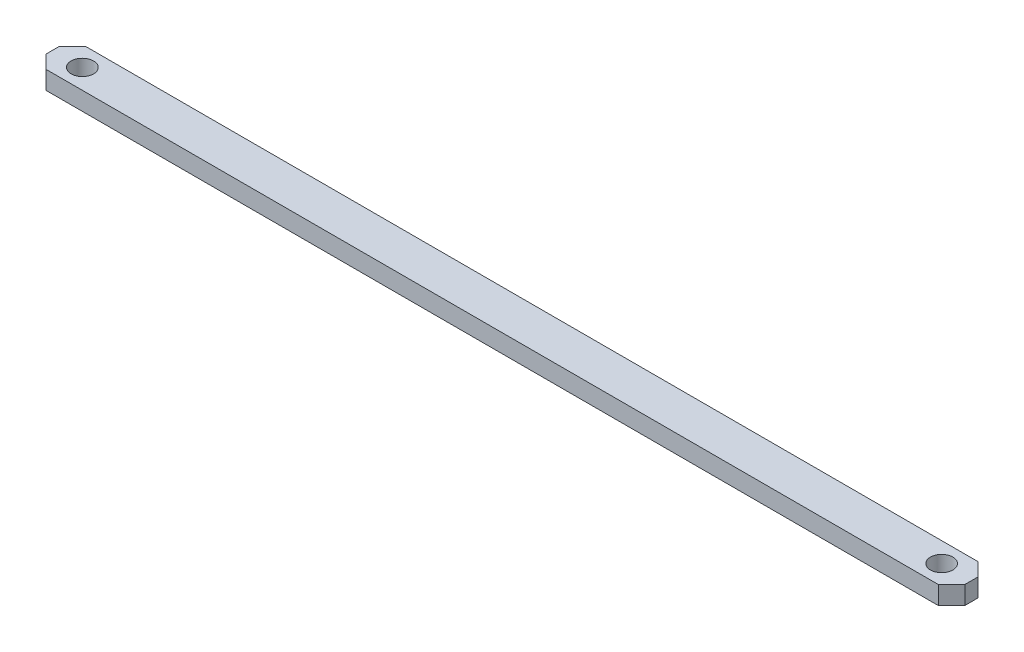
SolidWorks part; units mm, degrees
ref_plane "Front Plane" through (0, 0, 0) normal (0, 0, 1) x (1, 0, 0)
ref_plane "Top Plane" through (0, 0, 0) normal (0, 1, 0) x (1, 0, 0)
ref_plane "Right Plane" through (0, 0, 0) normal (1, 0, 0) x (0, 0, -1)
sketch "Sketch1" plane through (0, 0, 0) normal (0, 1, 0) x (1, 0, 0)
  line L1 (-69.5, 3) -> (69.5, 3)
  line L2 (-69.5, 3) -> (-69.5, -3)
  line L3 (-69.5, -3) -> (69.5, -3)
  line L4 (69.5, 3) -> (69.5, -3)
  line L5 (-69.5, 3) -> (69.5, -3) construction
  line L6 (-69.5, -3) -> (69.5, 3) construction
  point P0 (0, 0)
  point P5 (0, 0)
  dimension "D1" = 139
  dimension "D2" = 6
extrude "Boss-Extrude1" add sketch "Sketch1" along normal mid plane 2.76
sketch "Sketch8" plane through (0, 1.38, 0) normal (0, 1, 0) x (1, 0, 0)
  line L1 (0, 19.8498) -> (0, -13.2653) construction
  line L2 (0, -148.5615) -> (0, 69.4917) construction
  line L3 (69.5, -3) -> (69.5, 3) construction
  circle A0 centre (65, 0) radius 1.7
  circle A1 centre (-65, 0) radius 1.7
  dimension "D1" = 3.4
  dimension "D2" = 4.5
extrude "Cut-Extrude4" cut sketch "Sketch8" against normal through all both and the other way through all
chamfer "Chamfer2" distance 2 angle 45 4 edges at (-69.5, 0, 3) (-69.5, 0, -3) (69.5, 0, -3) (69.5, 0, 3)
